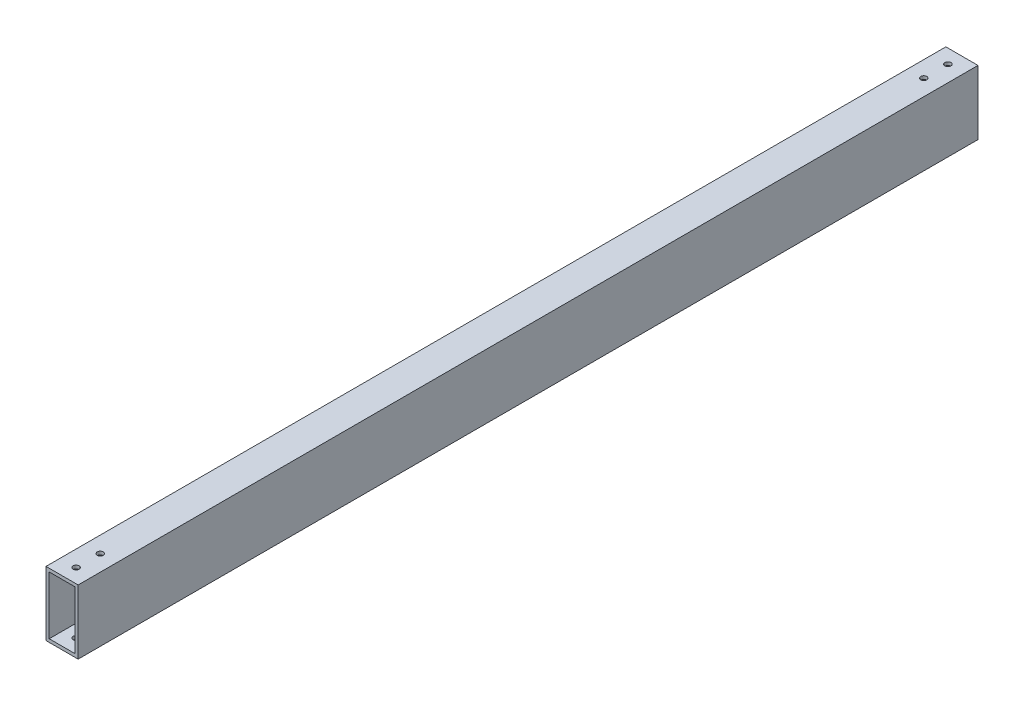
SolidWorks part; units mm, degrees
ref_plane "Front Plane" through (0, 0, 0) normal (0, 0, 1) x (1, 0, 0)
ref_plane "Top Plane" through (0, 0, 0) normal (0, 1, 0) x (1, 0, 0)
ref_plane "Right Plane" through (0, 0, 0) normal (1, 0, 0) x (0, 0, -1)
sketch "Sketch1" plane through (0, 0, 0) normal (0, 0, 1) x (1, 0, 0)
  line L1 (12.7, 25.4) -> (-12.7, 25.4)
  line L2 (12.7, 25.4) -> (12.7, -25.4)
  line L3 (12.7, -25.4) -> (-12.7, -25.4)
  line L4 (-12.7, 25.4) -> (-12.7, -25.4)
  line L5 (0, -25.4) -> (0, 25.4) construction
  line L6 (12.7, 0) -> (-12.7, 0) construction
  point P0 (0, 0)
  dimension "D1" = 25.4
  dimension "D2" = 50.8
extrude "Boss-Extrude1" add sketch "Sketch1" along normal mid plane 711.2
shell "Shell1" thickness 2.54
sketch "Sketch2" plane through (0, -25.4, 0) normal (0, -1, 0) x (1, 0, 0)
  line L0 (-12.7, 355.6) -> (12.7, 355.6) construction
  line L1 (0, 0) -> (35.7474, 0) construction
  circle A0 centre (0, 344.4875) radius 2.3813
  circle A1 centre (0, 325.4375) radius 2.3813
  circle A4 centre (0, -325.4375) radius 2.3813
  circle A5 centre (0, -344.4875) radius 2.3813
  dimension "D1" = 19.05
  dimension "D3" = 4.7625
  dimension "D2" = 11.1125
extrude "Cut-Extrude1" cut sketch "Sketch2" against normal through all
